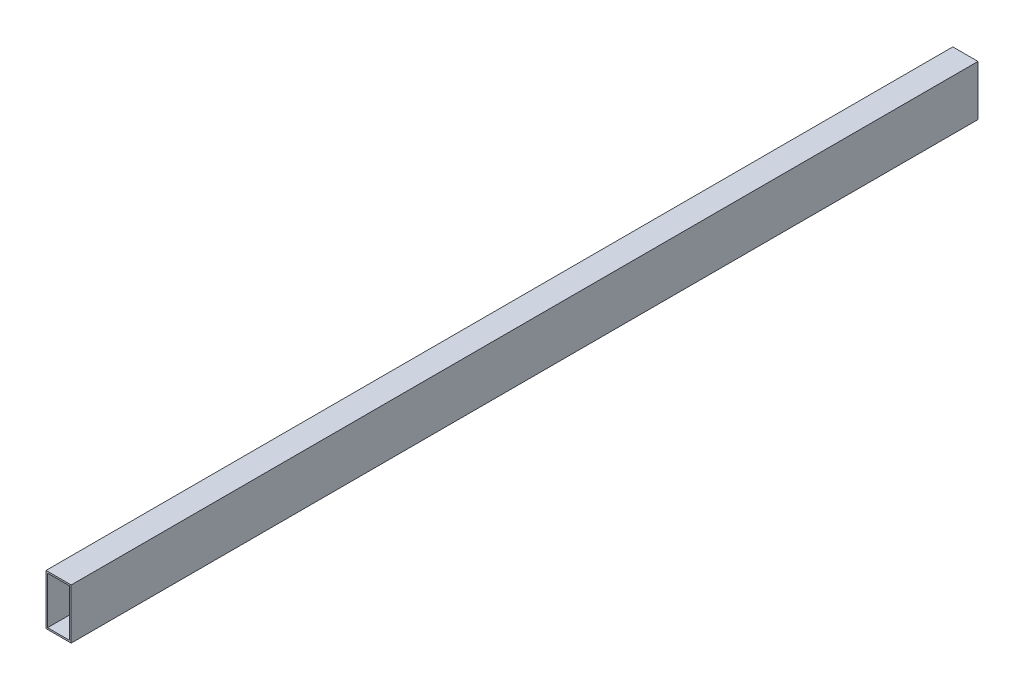
SolidWorks part; units mm, degrees
material "1060 Alloy"
ref_plane "Front Plane" through (0, 0, 0) normal (0, 0, 1) x (1, 0, 0)
ref_plane "Top Plane" through (0, 0, 0) normal (0, 1, 0) x (1, 0, 0)
ref_plane "Right Plane" through (0, 0, 0) normal (1, 0, 0) x (0, 0, -1)
sketch "Sketch1" plane through (0, 0, 0) normal (0, 0, 1) x (1, 0, 0)
  line L0 (-11.0998, -23.7998) -> (-11.0998, 23.7998)
  line L1 (-12.7, -25.4) -> (12.7, -25.4)
  line L2 (-12.7, -25.4) -> (-12.7, 25.4)
  line L3 (-12.7, 25.4) -> (12.7, 25.4)
  line L4 (12.7, -25.4) -> (12.7, 25.4)
  line L5 (-12.7, -25.4) -> (12.7, 25.4) construction
  line L6 (-12.7, 25.4) -> (12.7, -25.4) construction
  line L7 (-11.0998, 23.7998) -> (11.0998, 23.7998)
  line L8 (11.0998, -23.7998) -> (11.0998, 23.7998)
  line L9 (-11.0998, -23.7998) -> (11.0998, -23.7998)
  point P0 (0, 0)
  dimension "D1" = 50.8
  dimension "D2" = 25.4
  dimension "D3" = 1.6002
extrude "Boss-Extrude1" add sketch "Sketch1" against normal blind 914.4
